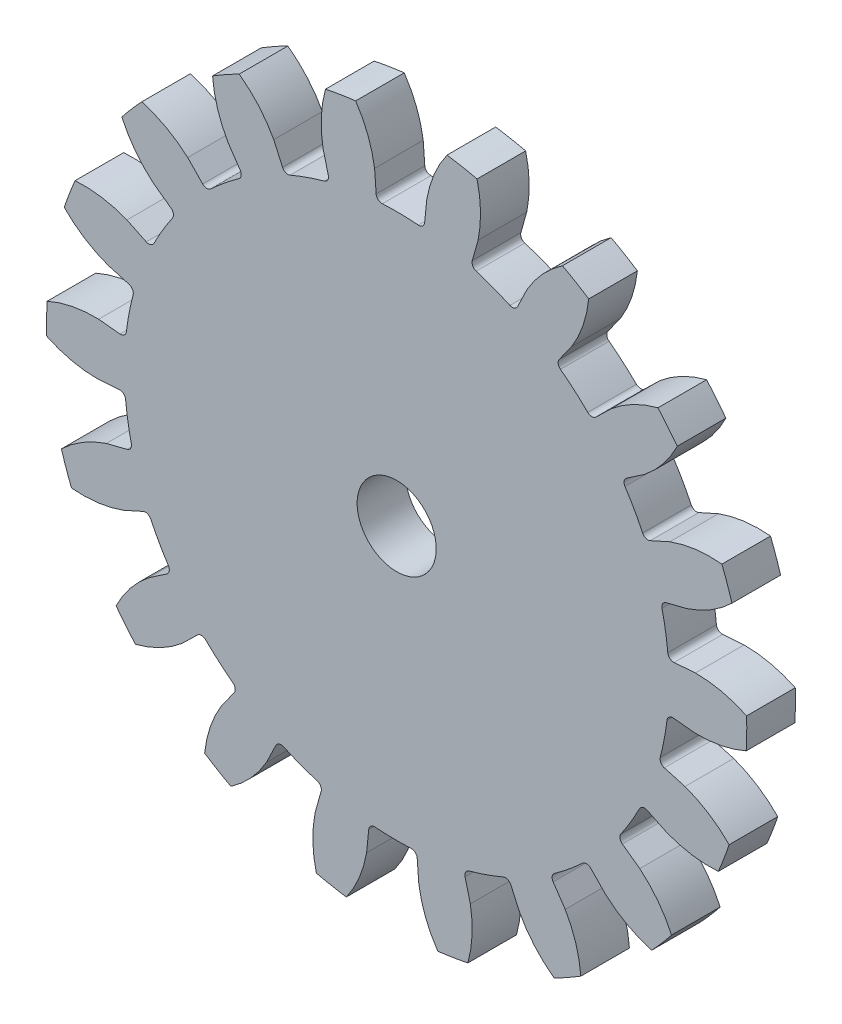
SolidWorks part; units mm, degrees
ref_plane "Front Plane" through (0, 0, 0) normal (0, 0, 1) x (1, 0, 0)
ref_plane "Top Plane" through (0, 0, 0) normal (0, 1, 0) x (1, 0, 0)
ref_plane "Right Plane" through (0, 0, 0) normal (1, 0, 0) x (0, 0, -1)
sketch "Sketch1" plane through (0, 0, 0) normal (0, 0, 1) x (1, 0, 0)
  line L0 (0, 0) -> (32.1433, 11.2137) construction
  line L1 (0, 0) -> (15.5157, 8.6828) construction
  line L2 (0, 0) -> (28.0547, 12.6272) construction
  line L3 (0, 0) -> (28.0655, 11.1868) construction
  line L4 (17.8347, 8.0273) -> (16.2134, 7.2975)
  line L5 (15.5157, 8.6828) -> (0, 0)
  line L7 (18.9577, 4.8083) -> (17.2343, 4.3712)
  line L8 (17.5497, 2.8525) -> (0, 0)
  circle A0 centre (0, 0) radius 22.86 construction
  circle A1 centre (0, 0) radius 17.78 construction
  circle A2 centre (0, 0) radius 19.558 construction
  arc A3 (17.8347, 8.0273) -> (21.2317, 8.4629) centre (20.4818, 0.8489) cw
  arc A4 (15.5157, 8.6828) -> (16.2134, 7.2975) centre (0, 0) cw
  arc A5 (21.2317, 8.4629) -> (21.8885, 6.5802) centre (0, 0) cw
  arc A6 (18.9577, 4.8083) -> (21.8885, 6.5802) centre (16.5652, 12.0755) ccw
  arc A7 (17.5497, 2.8525) -> (17.2343, 4.3712) centre (0, 0) ccw
  dimension "D1" = 10
  dimension "D4" = 1.5187
  dimension "D2" = 5
  dimension "D3" = 2.5
extrude "Boss-Extrude1" add sketch "Sketch1" along normal blind 3.175 contours L8 L5 A4 L4 A3 A5 A6 L7 A7
fillet "Fillet1" radius 0.381 2 edges at (16.2134, 7.2975, 1.5875) (17.2343, 4.3712, 1.5875)
pattern_circular "CirPattern1" count 18 every 20 about axis through (0, 0, 0) along (0, 0, 1) of "Boss-Extrude1", "Fillet1"
sketch "Sketch2" plane through (0, 0, 3.175) normal (0, 0, 1) x (1, 0, 0)
  line L0 (3.6669, -22.5601) -> (-3.6669, 22.5601) construction
  arc A0 (-2.6794, 22.6986) -> (-4.6475, 22.3787) centre (0, 0) ccw construction
  arc A1 (2.6794, -22.6986) -> (4.6475, -22.3787) centre (0, 0) ccw construction
  circle A2 centre (0, 0) radius 2.5828
extrude "Cut-Extrude1" cut sketch "Sketch2" against normal through all
